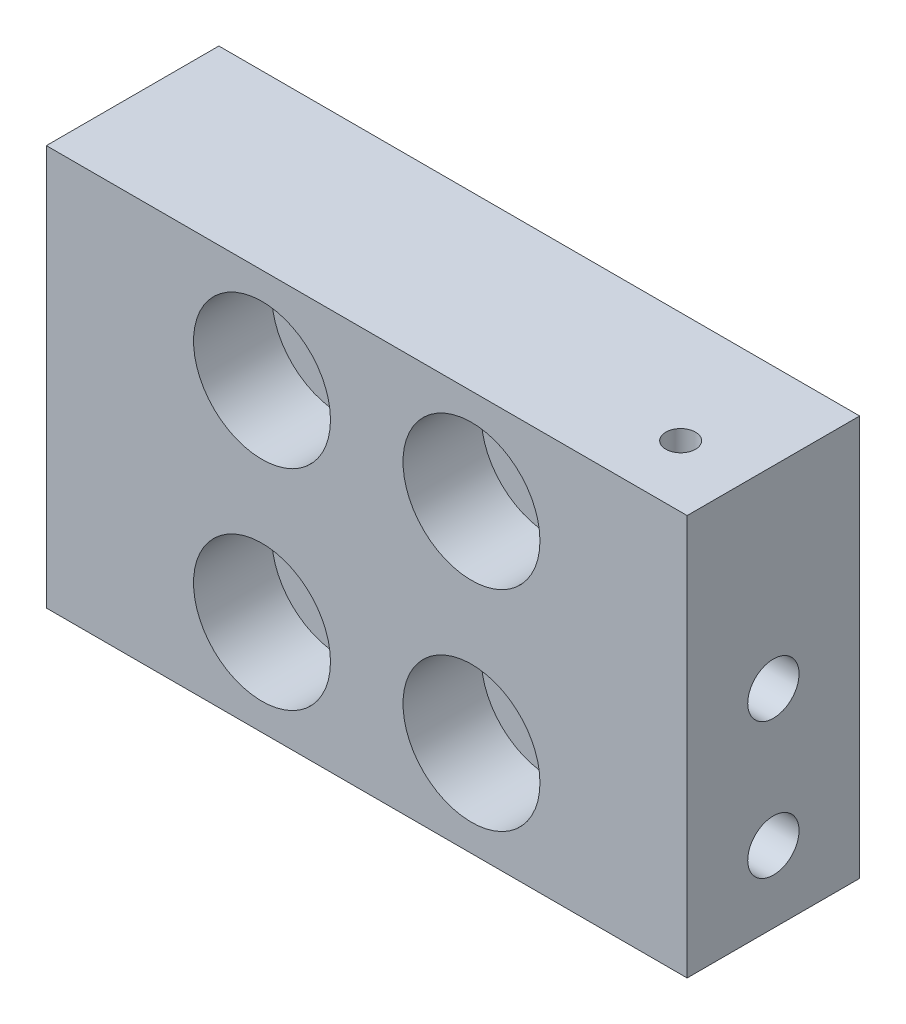
SolidWorks part; units mm, degrees
material "6061-T6 (SS)"
ref_plane "Front Plane" through (0, 0, 0) normal (0, 0, 1) x (1, 0, 0)
ref_plane "Top Plane" through (0, 0, 0) normal (0, 1, 0) x (1, 0, 0)
ref_plane "Right Plane" through (0, 0, 0) normal (1, 0, 0) x (0, 0, -1)
sketch "Sketch1" plane through (0, 0, 0) normal (0, 0, 1) x (1, 0, 0)
  line L1 (-17.5, -16.25) -> (17.5, -16.25)
  line L2 (-17.5, -16.25) -> (-17.5, 16.25)
  line L3 (-17.5, 16.25) -> (17.5, 16.25)
  line L4 (17.5, -16.25) -> (17.5, 16.25)
  line L5 (-17.5, -16.25) -> (17.5, 16.25) construction
  line L6 (-17.5, 16.25) -> (17.5, -16.25) construction
  point P0 (0, 0)
  dimension "D1" = 35
  dimension "D2" = 32.5
extrude "Boss-Extrude1" add sketch "Sketch1" along normal blind 14
hole_wizard "CBORE for 1/4 Socket Head Cap Screw1" positions "Sketch15" profile "Sketch17" counterbore size "1/4" standard "ANSI Inch" end condition through all
sketch "Sketch15" plane through (0, 0, 14) normal (0, 0, 1) x (1, 0, 0)
  line L16 (17.5, -16.25) -> (17.5, 16.25)
  line L17 (17.5, 16.25) -> (-17.5, 16.25)
  line L18 (-17.5, 16.25) -> (-17.5, -16.25)
  line L19 (-17.5, -16.25) -> (17.5, -16.25)
  line L23 (-17.5, -16.25) -> (17.5, -16.25)
  line L27 (0, -8.5) -> (0, 8.5) construction
  line L36 (17.5, -16.25) -> (17.5, 16.25) construction
  line L37 (17.5, -8.5) -> (17.5, -16.25) construction
  line L38 (17.5, 8.5) -> (17.5, 16.25) construction
  line L39 (-17.5, -16.25) -> (-17.5, -8.5) construction
  line L40 (-17.5, 8.5) -> (-17.5, 16.25) construction
  line L41 (0, 16.25) -> (0, 8.5) construction
  line L42 (17.5, 16.25) -> (-17.5, 16.25) construction
  line L44 (0, -16.25) -> (0, -8.5) construction
  point P2 (0, -8.5)
  point P4 (0, 8.5)
  dimension "D1" = 0
  dimension "D2" = 17
sketch "Sketch17" plane through (0, -8.5, 14) normal (1, 0, 0) x (0, -1, 0)
  line L0 (0, 0) -> (0, 14)
  line L1 (0, 14) -> (3.3782, 14)
  line L3 (3.3782, 14) -> (3.3782, 6.35)
  line L4 (3.3782, 6.35) -> (5.5562, 6.35)
  line L5 (5.5562, 6.35) -> (5.5563, 0)
  line L7 (5.5563, 0) -> (0, 0)
  line L11 (0, -6.35) -> (0, 107.95) construction
  dimension "Thru Hole Dia." = 6.7564
  dimension "Thru Hole Depth" = 14
  dimension "C'Bore Dia." = 11.1125
  dimension "C'Bore Depth" = 6.35
sketch "Sketch18" plane through (0, 16.25, 0) normal (0, 1, 0) x (1, 0, 0)
  line L0 (-17.5, -7) -> (17.5, -7) construction
  line L1 (-17.5, -14) -> (-17.5, 0) construction
  line L2 (17.5, -14) -> (17.5, 0) construction
  line L3 (0, 0) -> (0, -14) construction
  line L4 (17.5, -14) -> (-17.5, -14) construction
  line L5 (17.5, 0) -> (-17.5, 0) construction
  circle A0 centre (0, -7) radius 1.2065 construction
  circle A1 centre (11.9761, -9) radius 1.2065
  dimension "D1" = 2.413
  dimension "D2" = 2.413
  dimension "D3" = 11.9761
  dimension "D4" = 9
extrude "Spring-End Hole" cut sketch "Sketch18" against normal through all
sketch "Sketch19" plane through (0, 0, 14) normal (0, 0, 1) x (1, 0, 0)
  line L0 (-17.5, 16.25) -> (-17.5, -16.25) construction
  line L1 (-17.5, 16.25) -> (-17.5, -16.25)
  line L2 (-17.5, -16.25) -> (-34.5, -16.25)
  line L3 (-34.5, -16.25) -> (-34.5, 16.25)
  line L4 (-34.5, 16.25) -> (-17.5, 16.25)
  dimension "D1" = 17
extrude "Boss-Extrude2" add sketch "Sketch19" against normal up to surface (14 mm away) up to face at (3.3782, -8.5, 0)
hole_wizard "CBORE for 1/4 Socket Head Cap Screw2" positions "Sketch20" profile "Sketch21" counterbore size "1/4" standard "ANSI Inch" end condition through all
sketch "Sketch20" plane through (0, 0, 14) normal (0, 0, 1) x (1, 0, 0)
  line L0 (0, 8.5) -> (-17, 8.5) construction
  line L2 (0, -8.5) -> (-17, -8.5) construction
  circle A0 centre (0, 8.5) radius 3.3782 construction
  circle A1 centre (0, -8.5) radius 3.3782 construction
  circle A2 centre (0, 8.5) radius 3.3782
  circle A3 centre (0, -8.5) radius 3.3782
  point P0 (-17, 8.5)
  point P2 (-17, -8.5)
  dimension "D1" = 17
sketch "Sketch21" plane through (-17, 8.5, 14) normal (1, 0, 0) x (0, -1, 0)
  line L0 (0, 0) -> (0, 14)
  line L1 (0, 14) -> (3.3782, 14)
  line L3 (3.3782, 14) -> (3.3782, 6.35)
  line L4 (3.3782, 6.35) -> (5.5562, 6.35)
  line L5 (5.5562, 6.35) -> (5.5563, 0)
  line L7 (5.5563, 0) -> (0, 0)
  line L11 (0, -6.35) -> (0, 107.95) construction
  dimension "Thru Hole Dia." = 6.7564
  dimension "Thru Hole Depth" = 14
  dimension "C'Bore Dia." = 11.1125
  dimension "C'Bore Depth" = 6.35
ref_plane "Plane1" through (-8.5, 0, 0) normal (1, 0, 0) x (0, 0, -1)
sketch "Sketch22" plane through (-34.5, 0, 0) normal (-1, 0, 0) x (0, 0, 1)
  circle A0 centre (7, 0.5882) radius 2.0828
  circle A1 centre (7, -10.4354) radius 2.0828
  dimension "D1" = 4.1656
  dimension "D2" = 4.1656
extrude "Cut-Extrude1" cut sketch "Sketch22" against normal blind 10
mirror "Mirror1" about plane through (-8.5, 0, 0) normal (1, 0, 0) of "Cut-Extrude1"
